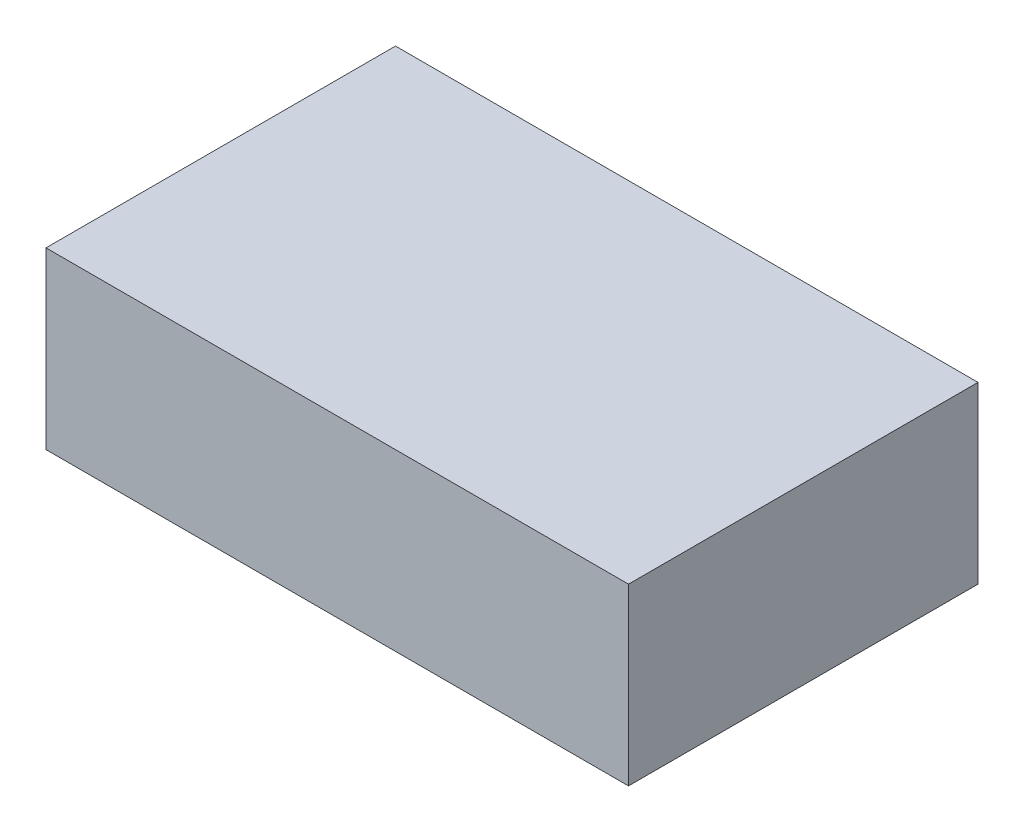
SolidWorks part; units mm, degrees
ref_plane "Front Plane" through (0, 0, 0) normal (0, 0, 1) x (1, 0, 0)
ref_plane "Top Plane" through (0, 0, 0) normal (0, 1, 0) x (1, 0, 0)
ref_plane "Right Plane" through (0, 0, 0) normal (1, 0, 0) x (0, 0, -1)
sketch "Sketch1" plane through (0, 0, 0) normal (0, 1, 0) x (1, 0, 0)
  line L1 (-50, 30) -> (50, 30)
  line L2 (-50, 30) -> (-50, -30)
  line L3 (-50, -30) -> (50, -30)
  line L4 (50, 30) -> (50, -30)
  point P4 (-50, 0)
  point P5 (0, 30)
extrude "Boss-Extrude1" add sketch "Sketch1" along normal blind 30
